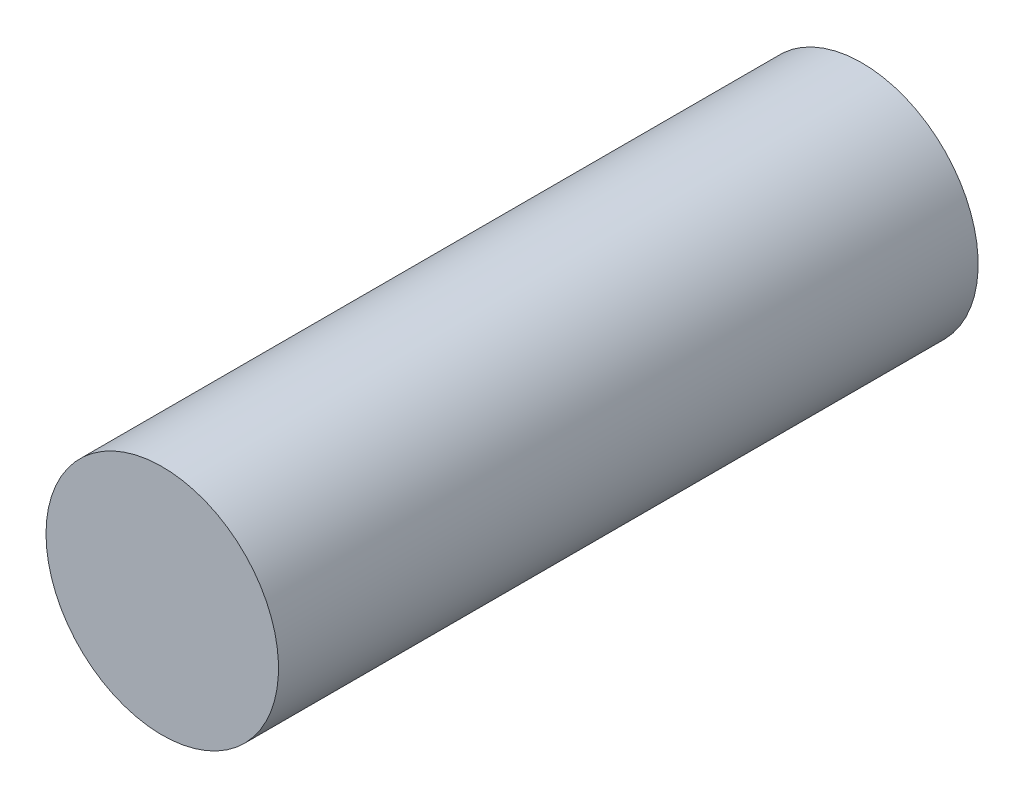
SolidWorks part; units mm, degrees
ref_plane "Front Plane" through (0, 0, 0) normal (1, 0, 0) x (0, 1, 0)
ref_plane "Top Plane" through (0, 0, 0) normal (0, 0, 1) x (0, 1, 0)
ref_plane "Right Plane" through (0, 0, 0) normal (0, 1, 0) x (-1, 0, 0)
sketch "Sketch1" plane through (0, 0, 0) normal (0, 0, 1) x (0, 1, 0)
  circle A0 centre (0, 0) radius 12.6619
  dimension "D1" = 25.3238
extrude "Boss-Extrude1" add sketch "Sketch1" along normal blind 76.2
